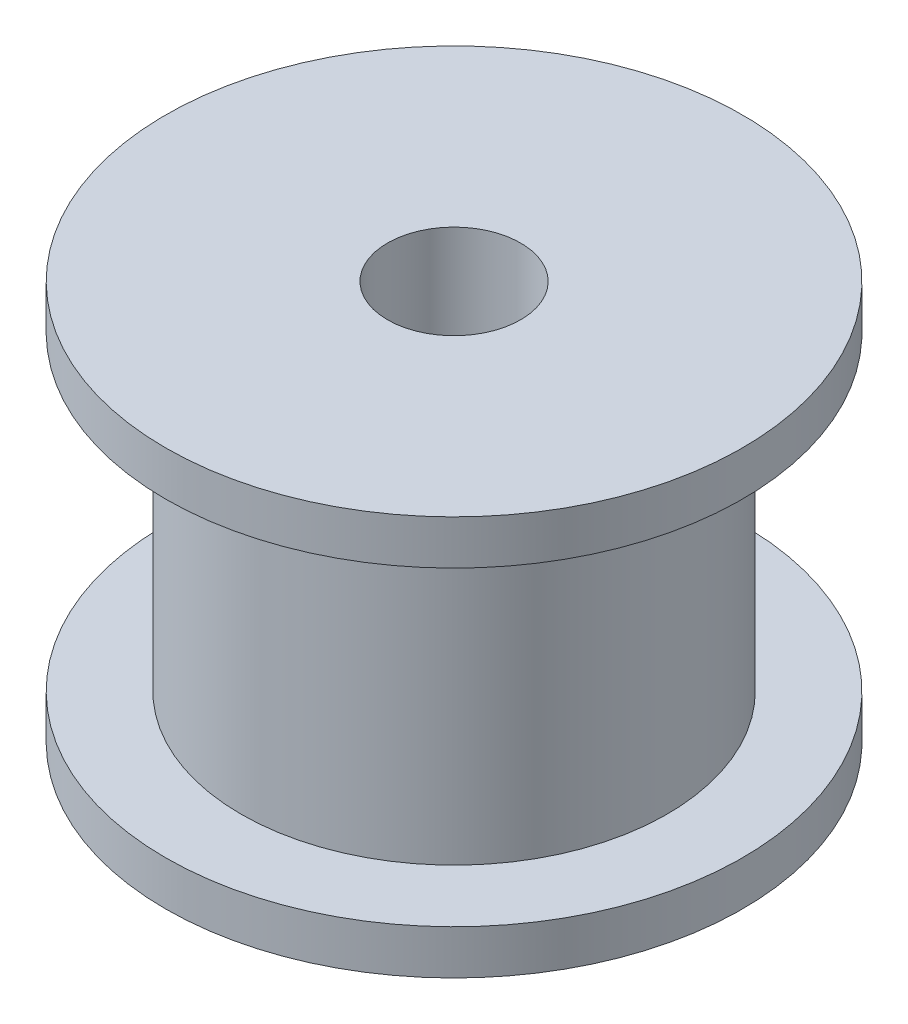
SolidWorks part; units mm, degrees
ref_plane "Front Plane" through (0, 0, 0) normal (0, 0, 1) x (1, 0, 0)
ref_plane "Top Plane" through (0, 0, 0) normal (0, 1, 0) x (1, 0, 0)
ref_plane "Right Plane" through (0, 0, 0) normal (1, 0, 0) x (0, 0, -1)
sketch "Sketch1" plane through (0, 0, 0) normal (0, 1, 0) x (1, 0, 0)
  circle A0 centre (0, 0) radius 1.5
  circle A1 centre (0, 0) radius 6.5
  dimension "D1" = 13
  dimension "D2" = 3
extrude "Boss-Extrude1" add sketch "Sketch1" along normal blind 1
sketch "Sketch2" plane through (0, 1, 0) normal (0, 1, 0) x (1, 0, 0)
  circle A0 centre (0, 0) radius 1.5
  circle A1 centre (0, 0) radius 4.8
  dimension "D1" = 9.6
extrude "Boss-Extrude2" add sketch "Sketch2" along normal blind 7
sketch "Sketch3" plane through (0, 8, 0) normal (0, 1, 0) x (1, 0, 0)
  circle A0 centre (0, 0) radius 1.5
  circle A1 centre (0, 0) radius 6.5
extrude "Boss-Extrude3" add sketch "Sketch3" along normal blind 1
